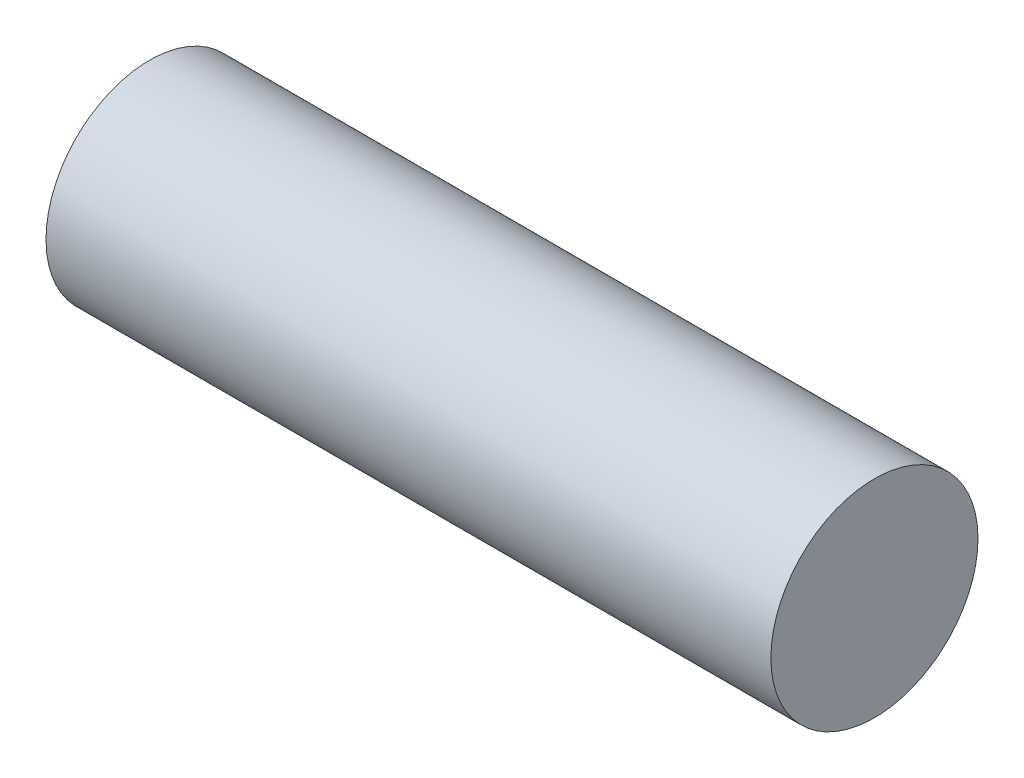
SolidWorks part; units mm, degrees
ref_plane "前视基准面" through (0, 0, 0) normal (0, 0, 1) x (1, 0, 0)
ref_plane "上视基准面" through (0, 0, 0) normal (0, 1, 0) x (1, 0, 0)
ref_plane "右视基准面" through (0, 0, 0) normal (1, 0, 0) x (0, 0, -1)
other "Configuration Table"
sketch "草图1" plane through (0, 0, 0) normal (1, 0, 0) x (0, 0, -1)
  circle A0 centre (0, 0) radius 2
extrude "凸台-拉伸1" add sketch "草图1" along normal blind 14
